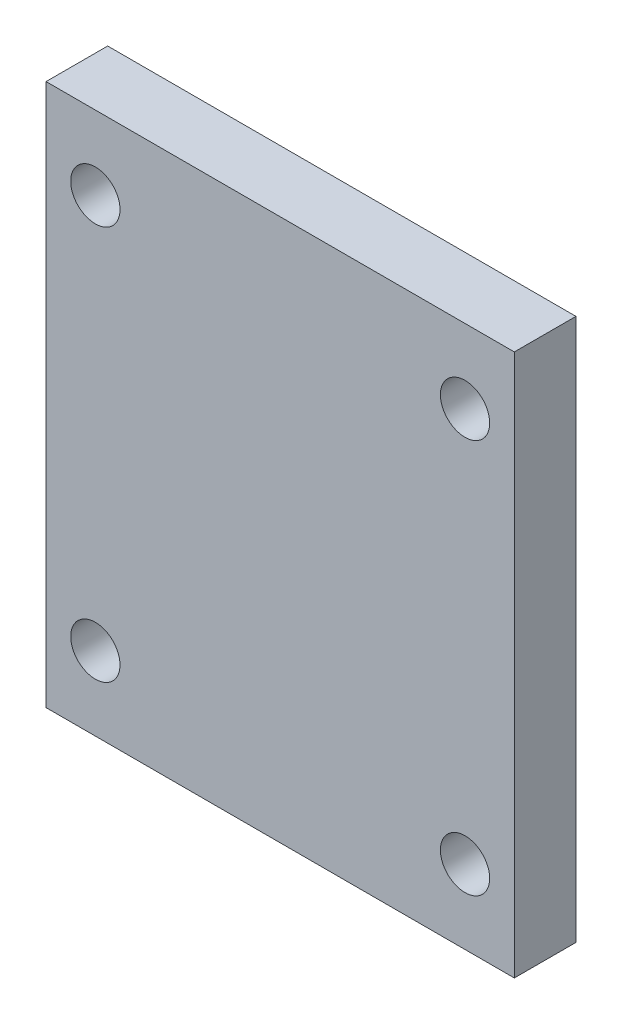
SolidWorks part; units mm, degrees
ref_plane "Front Plane" through (0, 0, 0) normal (0, 0, 1) x (1, 0, 0)
ref_plane "Top Plane" through (0, 0, 0) normal (0, 1, 0) x (1, 0, 0)
ref_plane "Right Plane" through (0, 0, 0) normal (1, 0, 0) x (0, 0, -1)
sketch "Sketch1" plane through (0, 0, 0) normal (0, 0, 1) x (1, 0, 0)
  line L1 (0, 0) -> (38, 0)
  line L2 (0, 0) -> (0, 44)
  line L3 (0, 44) -> (38, 44)
  line L4 (38, 0) -> (38, 44)
  circle A0 centre (4, 38) radius 2
  circle A1 centre (34, 38) radius 2
  circle A2 centre (34, 6) radius 2
  circle A3 centre (4, 6) radius 2
  dimension "D3" = 6
  dimension "D11" = 4
  dimension "D12" = 4
  dimension "D13" = 4
  dimension "D14" = 4
  dimension "D1" = 38
  dimension "D2" = 44
  dimension "D4" = 4
  dimension "D5" = 4
  dimension "D6" = 6
  dimension "D7" = 6
  dimension "D8" = 4
  dimension "D9" = 4
  dimension "D10" = 6
extrude "Boss-Extrude1" add sketch "Sketch1" along normal blind 5
